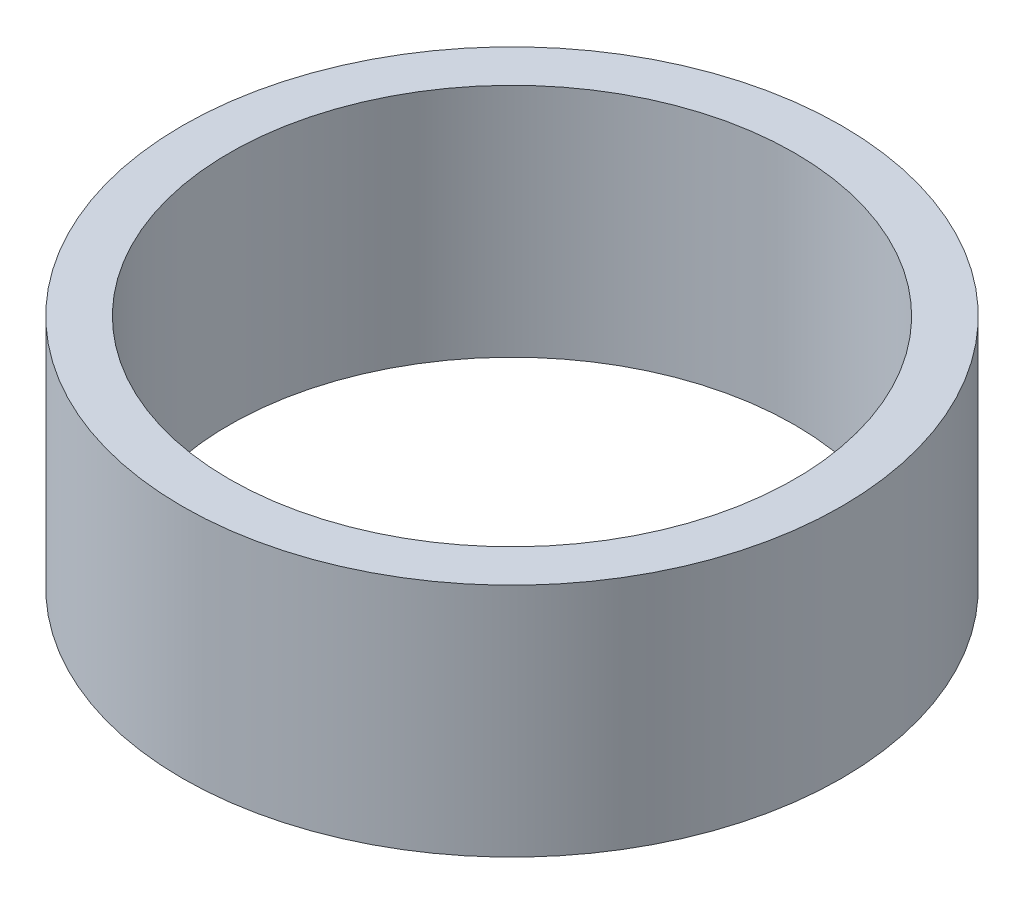
SolidWorks part; units mm, degrees
ref_plane "Front Plane" through (0, 0, 0) normal (0, 0, 1) x (1, 0, 0)
ref_plane "Top Plane" through (0, 0, 0) normal (0, 1, 0) x (1, 0, 0)
ref_plane "Right Plane" through (0, 0, 0) normal (1, 0, 0) x (0, 0, -1)
sketch "Sketch1" plane through (0, 0, 0) normal (0, 1, 0) x (1, 0, 0)
  circle A0 centre (0, 0) radius 19.05
  circle A1 centre (0, 0) radius 22.225
  dimension "D1" = 38.1
  dimension "D2" = 44.45
extrude "Boss-Extrude1" add sketch "Sketch1" along normal blind 15.875
